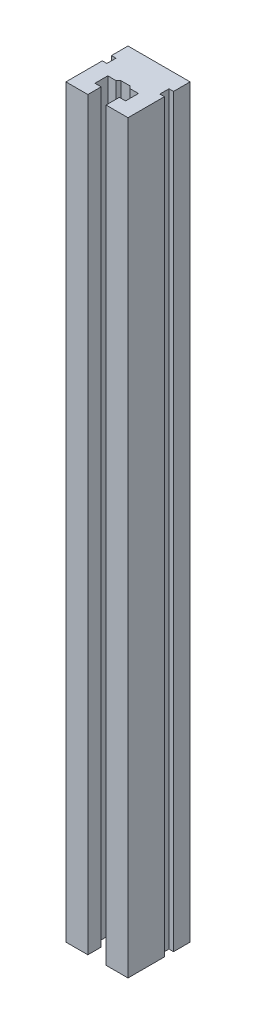
SolidWorks part; units mm, degrees
material "1.2210 (115CrV3)"
ref_plane "Front Plane" through (0, 0, 0) normal (0, 0, 1) x (1, 0, 0)
ref_plane "Top Plane" through (0, 0, 0) normal (0, 1, 0) x (1, 0, 0)
ref_plane "Right Plane" through (0, 0, 0) normal (1, 0, 0) x (0, 0, -1)
sketch "Sketch1" plane through (0, 0, 0) normal (0, 1, 0) x (1, 0, 0)
  line L0 (37.5, 0) -> (-37.5, 0)
  line L1 (-37.5, 0) -> (-37.5, -20)
  line L2 (-37.5, -20) -> (-32, -20)
  line L3 (-32, -20) -> (-32, -31)
  line L4 (-32, -31) -> (-37.5, -31)
  line L5 (-37.5, -31) -> (-37.5, -75)
  line L6 (-37.5, -75) -> (-11, -75)
  line L7 (37.5, -75) -> (37.5, -31)
  line L8 (37.5, -31) -> (32, -31)
  line L9 (32, -31) -> (32, -20)
  line L10 (32, -20) -> (37.5, -20)
  line L11 (37.5, -20) -> (37.5, 0)
  line L12 (-11, -75) -> (-11, -58.9)
  line L13 (-11, -58.9) -> (-18.5, -58.9)
  line L14 (-18.5, -58.9) -> (-18.5, -43.4)
  line L15 (-18.5, -43.4) -> (-8.4, -43.4)
  line L16 (18.5, -43.4) -> (18.5, -58.9)
  line L17 (18.5, -58.9) -> (11, -58.9)
  line L18 (11, -58.9) -> (11, -75)
  line L19 (11, -75) -> (37.5, -75)
  line L20 (0, 12.3611) -> (0, -58.9776) construction
  line L21 (8.4, -43.4) -> (5.5, -40.5)
  line L22 (5.5, -40.5) -> (-5.5, -40.5)
  line L23 (-5.5, -40.5) -> (-8.4, -43.4)
  line L24 (8.4, -43.4) -> (18.5, -43.4)
  dimension "D1" = 11
  dimension "D2" = 90
  dimension "C" = 75
  dimension "L" = 20
  dimension "G" = 75
  dimension "D3" = 11
  dimension "D4" = 34.5
  dimension "D5" = 31.6
  dimension "D6" = 16.1
  dimension "D7" = 22
  dimension "D8" = 37
  dimension "D9" = 5.5
extrude "Boss-Extrude1" add sketch "Sketch1" against normal blind 900
